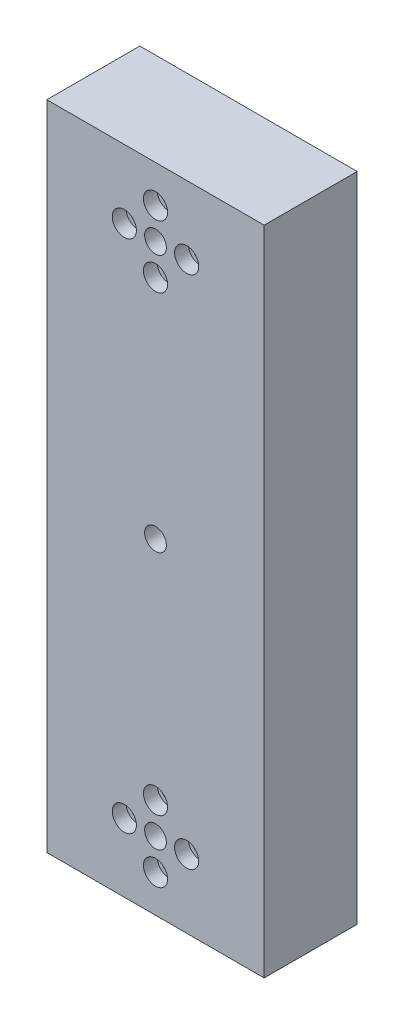
SolidWorks part; units mm, degrees
material "6061-T6 (SS)"
ref_plane "Front Plane" through (0, 0, 0) normal (1, 0, 0) x (0, 1, 0)
ref_plane "Top Plane" through (0, 0, 0) normal (0, 0, 1) x (0, 1, 0)
ref_plane "Right Plane" through (0, 0, 0) normal (0, 1, 0) x (-1, 0, 0)
sketch "Sketch1" plane through (0, 0, 0) normal (0, 0, 1) x (0, 1, 0)
  line L0 (-150, 0) -> (150, 0) construction
  line L1 (-150, -50) -> (150, -50)
  line L2 (-150, -50) -> (-150, 50)
  line L3 (-150, 50) -> (150, 50)
  line L4 (150, -50) -> (150, 50)
  line L7 (0, 0) -> (0, 50) construction
  circle A0 centre (0, 0) radius 5
  circle A1 centre (-118.5, 0) radius 5
  circle A2 centre (-118.5, 0) radius 14.351 construction
  circle A3 centre (118.5, 0) radius 5
  circle A4 centre (118.5, 0) radius 14.351 construction
  point P0 (0, 0)
  point P14 (-104.149, 0)
  point P15 (-118.5, 14.351)
  point P16 (-132.851, 0)
  point P17 (-118.5, -14.351)
  point P21 (104.149, 0)
  point P22 (118.5, -14.351)
  point P23 (132.851, 0)
  point P24 (118.5, 14.351)
  point P25 (0, 0)
  dimension "D3" = 10
  dimension "D5" = 28.702
  dimension "D1" = 300
  dimension "D2" = 100
  dimension "D4" = 31.5
extrude "Boss-Extrude1" add sketch "Sketch1" against normal blind 42.8
hole_wizard "CBORE for 1/4 Socket Head Cap Screw1" positions "Sketch2" profile "Sketch3" counterbore size "1/4" standard "ANSI Inch" end condition through all
sketch "Sketch2" plane through (0, 0, 0) normal (0, 0, 1) x (0, -1, 0)
  point P0 (118.5, 14.351)
  point P3 (132.851, 0)
  point P6 (118.5, -14.351)
  point P9 (104.149, 0)
  point P12 (-104.149, 0)
  point P15 (-118.5, 14.351)
  point P18 (-132.851, 0)
  point P21 (-118.5, -14.351)
sketch "Sketch3" plane through (14.351, -118.5, 0) normal (1, 0, 0) x (0, -1, 0)
  line L0 (0, 0) -> (0, 42.8)
  line L1 (0, 42.8) -> (3.5687, 42.8)
  line L3 (3.5687, 42.8) -> (3.5687, 6.35)
  line L4 (3.5687, 6.35) -> (5.5562, 6.35)
  line L5 (5.5562, 6.35) -> (5.5562, 0)
  line L7 (5.5562, 0) -> (0, 0)
  line L11 (0, -6.35) -> (0, 107.95) construction
  dimension "Thru Hole Dia." = 7.1374
  dimension "Thru Hole Depth" = 42.8
  dimension "C'Bore Dia." = 11.1125
  dimension "C'Bore Depth" = 6.35
